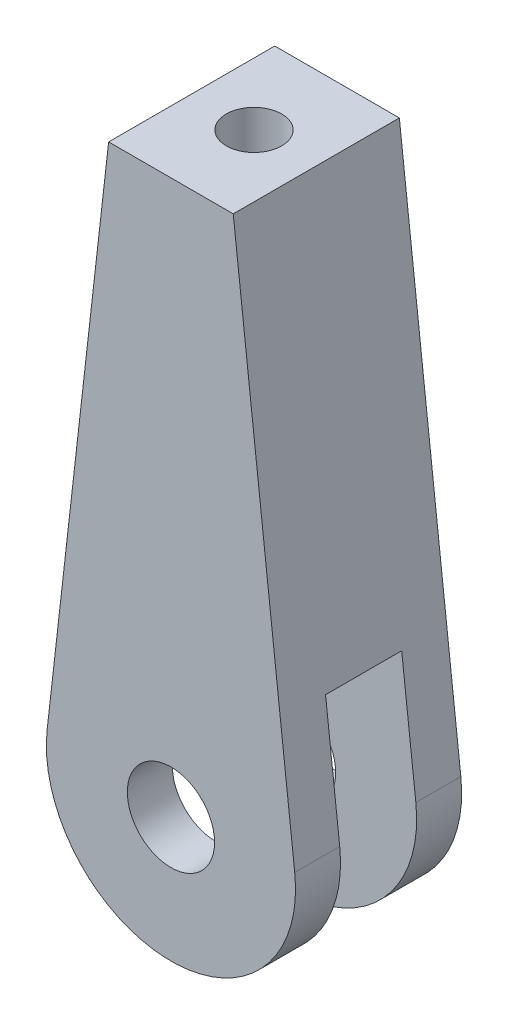
SolidWorks part; units mm, degrees
material "ABS"
ref_plane "Front Plane" through (0, 0, 0) normal (0, 0, 1) x (1, 0, 0)
ref_plane "Top Plane" through (0, 0, 0) normal (0, 1, 0) x (1, 0, 0)
ref_plane "Right Plane" through (0, 0, 0) normal (1, 0, 0) x (0, 0, -1)
sketch "Sketch1" plane through (0, 0, 0) normal (0, 0, 1) x (1, 0, 0)
  line L0 (0, 0) -> (0, 40) construction
  line L1 (4.5, 40) -> (-4.5, 40)
  line L2 (4.5, 40) -> (8.9421, 1.019)
  line L3 (-4.5, 40) -> (-8.9421, 1.019)
  arc A0 (-8.9421, 1.019) -> (8.9421, 1.019) centre (0, 0) ccw
  point P7 (0, 40)
  dimension "D1" = 18
  dimension "D2" = 40
  dimension "D3" = 9
extrude "Boss-Extrude1" add sketch "Sketch1" along normal blind 12
sketch "Sketch2" plane through (0, 0, 0) normal (0, 0, -1) x (-1, 0, 0)
  circle A0 centre (0, 0) radius 6.775
  dimension "D1" = 13.55
extrude "Cut-Extrude1" [suppressed] cut sketch "Sketch2" against normal blind 5.2
sketch "Sketch3" [suppressed] plane through (0, 0, 5.2) normal (0, 0, -1) x (-1, 0, 0)
  circle A0 centre (0, 0) radius 2.15
  dimension "D1" = 4.3
extrude "Cut-Extrude2" [suppressed] cut sketch "Sketch3" against normal through all
sketch "Sketch4" plane through (0, 0, 12) normal (0, 0, 1) x (1, 0, 0)
  circle A0 centre (0, 0) radius 4.05
  dimension "D1" = 8.1
extrude "Cut-Extrude3" [suppressed] cut sketch "Sketch4" against normal blind 3
sketch "Sketch5" plane through (0, 40, 0) normal (0, 1, 0) x (1, 0, 0)
  line L1 (0, 0) -> (0, -12) construction
  line L3 (4.5, -12) -> (-4.5, -12) construction
  circle A0 centre (0, -6) radius 2
  point P10 (0, -6)
  dimension "D1" = 4
extrude "Cut-Extrude4" cut sketch "Sketch5" against normal blind 12.5
sketch "Sketch7" plane through (0, 0, 0) normal (0, 0, 1) x (1, 0, 0)
  circle A0 centre (0, 0) radius 3.15
  dimension "D1" = 6.3
sketch "Sketch9" plane through (0, 0, 0) normal (0, 1, 0) x (1, 0, 0)
  line L1 (-9.9691, -3.25) -> (9.9691, -3.25)
  line L2 (-9.9691, -3.25) -> (-9.9691, -8.75)
  line L3 (-9.9691, -8.75) -> (9.9691, -8.75)
  line L4 (9.9691, -3.25) -> (9.9691, -8.75)
  line L5 (-9.9691, -3.25) -> (9.9691, -8.75) construction
  line L6 (-9.9691, -8.75) -> (9.9691, -3.25) construction
  point P0 (0, -6)
  dimension "D1" = 5.5
extrude "Cut-Extrude6" cut sketch "Sketch9" against normal blind 16 and the other way blind 10
extrude "Cut-Extrude8" cut sketch "Sketch7" against normal through all and the other way through all
